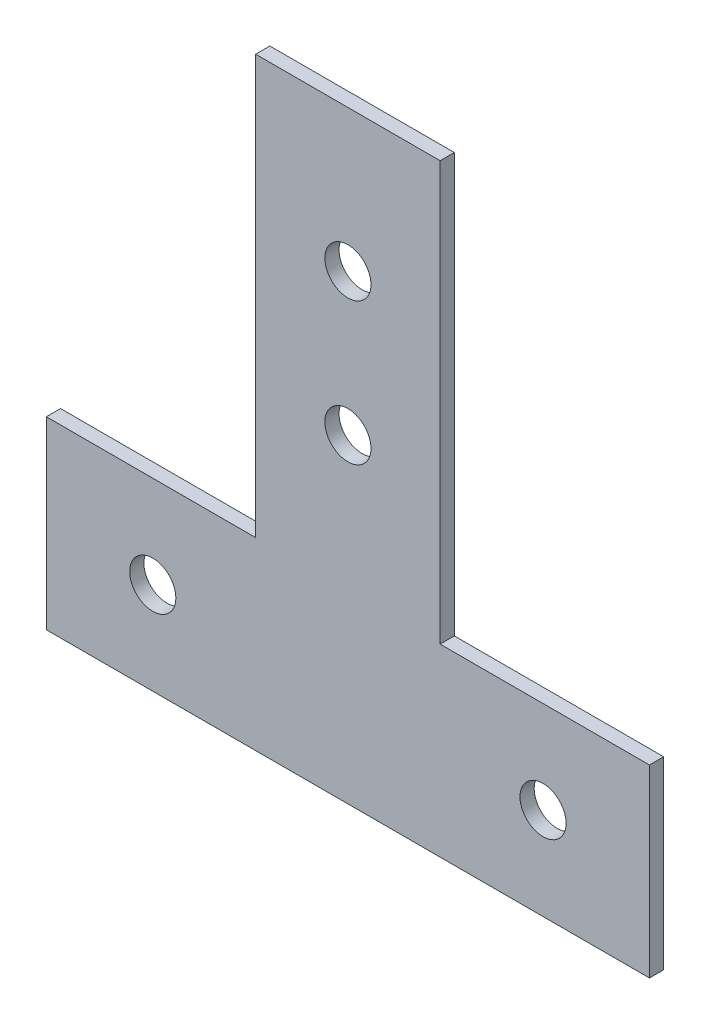
SolidWorks part; units mm, degrees
ref_plane "前视基准面" through (0, 0, 0) normal (0, 0, 1) x (1, 0, 0)
ref_plane "上视基准面" through (0, 0, 0) normal (0, 1, 0) x (1, 0, 0)
ref_plane "右视基准面" through (0, 0, 0) normal (1, 0, 0) x (0, 0, -1)
sketch "草图1" plane through (0, 0, 0) normal (0, 0, 1) x (1, 0, 0)
  line L1 (-42.5, -13) -> (42.5, -13)
  line L2 (-42.5, -13) -> (-42.5, 13)
  line L3 (-42.5, 13) -> (-13, 13)
  line L4 (42.5, -13) -> (42.5, 13)
  line L5 (-42.5, -13) -> (42.5, 13) construction
  line L6 (-42.5, 13) -> (42.5, -13) construction
  line L9 (-13, 72) -> (13, 72)
  line L10 (13, 13) -> (42.5, 13)
  line L11 (-13, 13) -> (-13, 72)
  line L12 (13, 13) -> (13, 72)
  point P0 (0, 0)
  point P6 (0, 72)
  dimension "D1" = 26
  dimension "D2" = 85
  dimension "D3" = 26
  dimension "D4" = 85
extrude "凸台-拉伸1" add sketch "草图1" along normal blind 2
sketch "草图2" plane through (0, 0, 2) normal (0, 0, 1) x (1, 0, 0)
  line L0 (0, 0) -> (0, 16.8919) construction
  line L2 (-42.5, 13) -> (-42.5, -13) construction
  line L3 (13, 72) -> (-13, 72) construction
  circle A0 centre (0, 52) radius 3.25
  circle A1 centre (0, 32) radius 3.25
  circle A2 centre (-27.5, 0) radius 3.25
  circle A3 centre (27.5, 0) radius 3.25
  dimension "D1" = 6.5
  dimension "D2" = 6.5
  dimension "D3" = 6.5
  dimension "D4" = 15
  dimension "D5" = 20
  dimension "D6" = 20
extrude "切除-拉伸1" cut sketch "草图2" against normal through all
